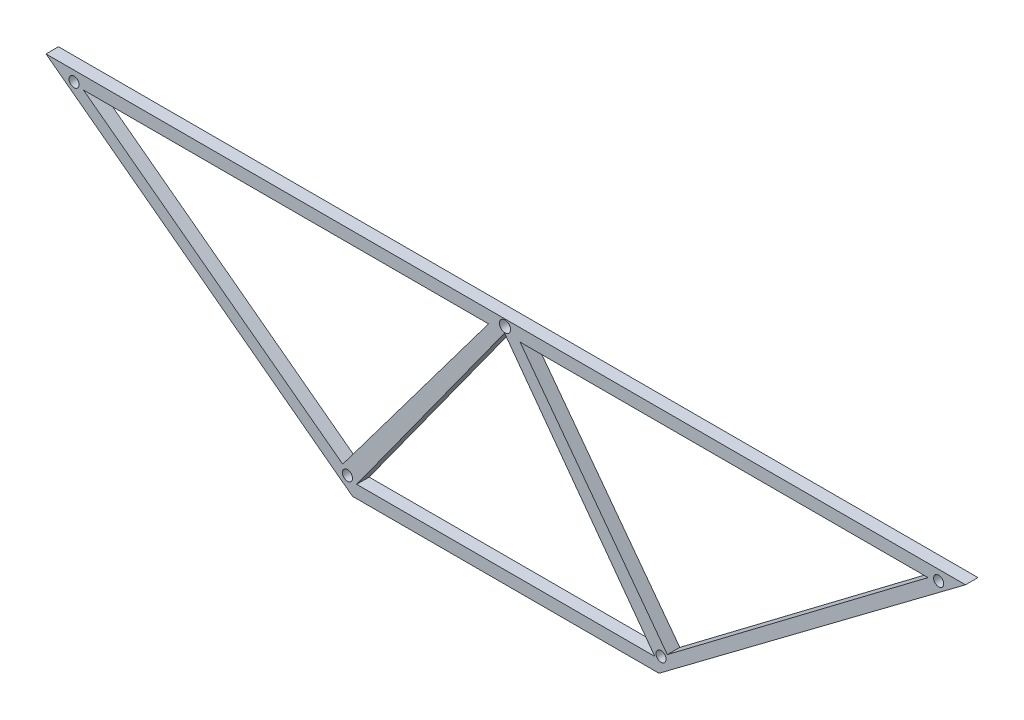
SolidWorks part; units mm, degrees
material "ASTM A36 Steel"
ref_plane "Front Plane" through (0, 0, 0) normal (0, 0, 1) x (1, 0, 0)
ref_plane "Top Plane" through (0, 0, 0) normal (0, 1, 0) x (1, 0, 0)
ref_plane "Right Plane" through (0, 0, 0) normal (1, 0, 0) x (0, 0, -1)
sketch "Sketch1" plane through (0, 0, 0) normal (0, 0, 1) x (1, 0, 0)
  line L0 (-800, 300) -> (400, 300)
  line L1 (0, 0) -> (-400, 0)
  line L2 (0, 0) -> (400, 300)
  line L3 (-800, 300) -> (-400, 0)
  line L4 (-394.5633, 16.31) -> (-5.4367, 16.31)
  line L5 (-5.4367, 16.31) -> (-201.528, 283.69)
  line L6 (-201.528, 283.69) -> (-394.5633, 16.31)
  dimension "D1" = 400
  dimension "D2" = 1200
  dimension "D3" = 500
  dimension "D4" = 500
  dimension "D5" = 16.31
  dimension "D6" = 16.31
  dimension "D7" = 16.31
  dimension "D8" = 16.31
extrude "Boss-Extrude1" add sketch "Sketch1" against normal blind 16.31
sketch "Sketch2" plane through (0, 0, 0) normal (0, 0, 1) x (1, 0, 0)
  line L0 (-751.07, 283.69) -> (-222.4887, 283.69)
  line L1 (400, 300) -> (-800, 300) construction
  line L2 (-800, 300) -> (-400, 0) construction
  line L3 (-751.07, 283.69) -> (-412.778, 29.971)
  line L4 (-222.4887, 283.69) -> (-412.778, 29.971)
  line L6 (-181.302, 283.69) -> (351.07, 283.69)
  line L7 (-181.302, 283.69) -> (10.8733, 26.5463)
  line L8 (10.8733, 26.5463) -> (351.07, 283.69)
  line L9 (-5.4367, 16.31) -> (-201.528, 283.69) construction
  line L10 (0, 0) -> (400, 300) construction
  dimension "D1" = 16.31
  dimension "D2" = 16.31
  dimension "D3" = 16.31
  dimension "D4" = 16.31
  dimension "D6" = 16.31
  dimension "D7" = 16.31
extrude "Cut-Extrude4" cut sketch "Sketch2" against normal blind 130.31 contours L7 L8 L6 | L0 L4 L3
sketch "Sketch3" plane through (0, 0, 0) normal (0, 0, 1) x (1, 0, 0)
  circle A0 centre (-200.9963, 291.5564) radius 7.316
  circle A1 centre (-763.3699, 286.7708) radius 6.6
  circle A2 centre (364.965, 286.7708) radius 6.6
  circle A3 centre (2.6133, 20.3732) radius 6.6
  circle A4 centre (-406.5778, 20.3732) radius 6.6
extrude "Cut-Extrude6" cut sketch "Sketch3" against normal blind 130.31
